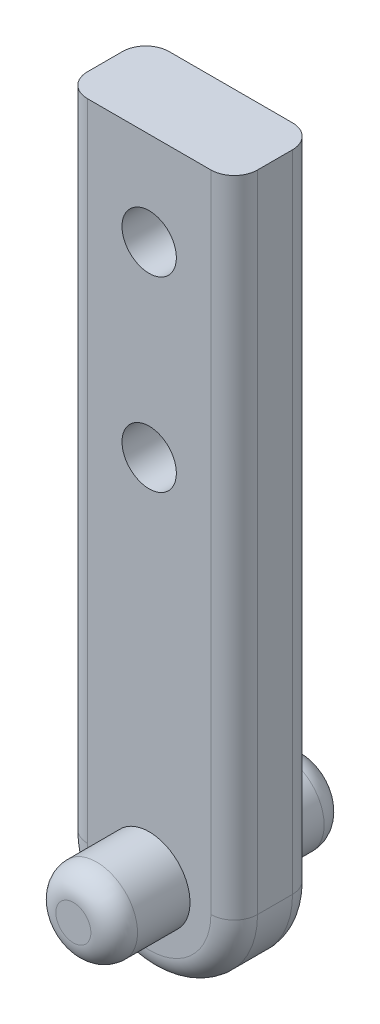
SolidWorks part; units mm, degrees
ref_plane "Front Plane" through (0, 0, 0) normal (0, 0, 1) x (1, 0, 0)
ref_plane "Top Plane" through (0, 0, 0) normal (0, 1, 0) x (1, 0, 0)
ref_plane "Right Plane" through (0, 0, 0) normal (1, 0, 0) x (0, 0, -1)
sketch "Sketch1" plane through (0, 0, 0) normal (0, 0, 1) x (1, 0, 0)
  line L0 (20.5792, 13.6635) -> (20.5792, 57.5511)
  line L1 (9.0039, 13.6635) -> (9.0039, 57.5511)
  line L2 (9.0039, 57.5511) -> (20.5792, 57.5511)
  line L4 (14.7916, 19.4511) -> (20.5792, 19.4511) construction
  arc A1 (14.7916, 10.4885) -> (14.7916, 16.8385) centre (14.7916, 13.6635) ccw construction
  arc A2 (20.5792, 13.6635) -> (9.0039, 13.6635) centre (14.7916, 13.6635) cw
  arc A3 (14.7916, 10.4885) -> (14.7916, 16.8385) centre (14.7916, 13.6635) ccw construction
  circle A4 centre (14.7916, 13.6635) radius 3.175 construction
  arc A5 (14.9008, 7.8769) -> (14.6823, 19.4501) centre (14.7916, 13.6635) ccw construction
  circle A6 centre (14.7916, 13.6635) radius 5.7876 construction
  dimension "D1" = 38.1
extrude "Boss-Extrude1" add sketch "Sketch1" along normal offset from surface 0.3969 and the other way offset from surface (2.7781 mm away) 0.3969
sketch "Sketch2" plane through (0, 0, 0) normal (0, 0, 1) x (1, 0, 0)
  circle A0 centre (14.7916, 13.6635) radius 2.7781
  dimension "D1" = 5.5562
extrude "Boss-Extrude2" add sketch "Sketch2" along normal mid plane 15.875
sketch "Sketch4" plane through (0, 0, 2.7781) normal (0, 0, 1) x (1, 0, 0)
  line L0 (14.7916, -940.4594) -> (14.7916, 49059.5406) construction
  line L1 (9.0039, 57.5511) -> (20.5792, 57.5511) construction
  point P1 (14.7916, 51.2011)
  point P5 (14.7916, 57.5511)
  point P6 (14.7916, 38.5011)
  dimension "D1" = 6.35
  dimension "D2" = 12.7
hole_wizard "#97 (0.0059) Diameter Hole1" positions "Sketch6" profile "Sketch5" hole size "#97" standard "ANSI Inch" end condition through all
sketch "Sketch6" plane through (0, 0, 2.7781) normal (0, 0, 1) x (1, 0, 0)
  point P0 (14.7916, 51.2011)
  point P3 (14.7916, 38.5011)
sketch "Sketch5" plane through (14.7916, 51.2011, 2.7781) normal (1, 0, 0) x (0, -1, 0)
  line L0 (0, 0) -> (0, 10.7156)
  line L1 (0, 10.7156) -> (1.85, 10.7156)
  line L2 (1.85, 10.7156) -> (1.85, 0)
  line L5 (1.85, 0) -> (0, 0)
  line L11 (0, -6.35) -> (0, 107.95) construction
  dimension "Thru Hole Dia." = 3.7
  dimension "Thru Hole Depth" = 10.7156
fillet "Fillet1" radius 1.5875 2 edges at (17.5697, 13.6635, -7.9375) (17.5697, 13.6635, 7.9375)
fillet "Fillet2" radius 1.5875 6 edges at (9.0039, 35.6073, 2.7781) (9.0039, 35.6073, -2.7781) (20.5792, 35.6073, 2.7781) (20.5792, 35.6073, -2.7781) (14.7916, 7.8758, 2.7781) (14.7916, 7.8758, -2.7781)
